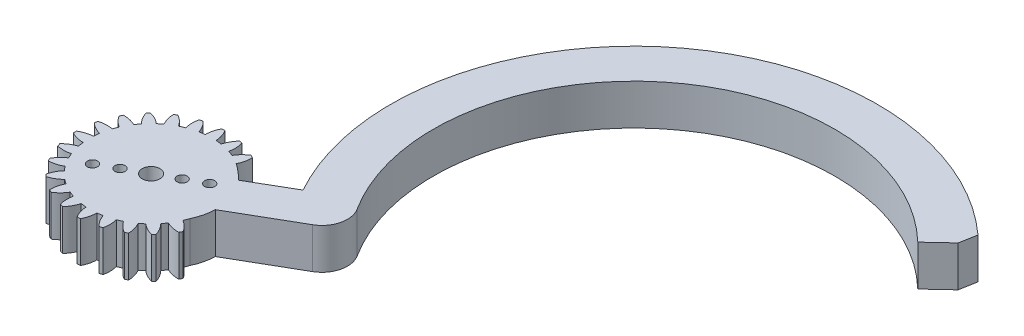
SolidWorks part; units mm, degrees
ref_plane "Alzado" through (0, 0, 0) normal (0, 0, 1) x (1, 0, 0)
ref_plane "Planta" through (0, 0, 0) normal (0, 1, 0) x (1, 0, 0)
ref_plane "Vista lateral" through (0, 0, 0) normal (1, 0, 0) x (0, 0, -1)
sketch "Croquis3" plane through (0, 0, 0) normal (0, 1, 0) x (1, 0, 0)
  line L0 (0, 0) -> (1.7285, 0.2738) construction
  line L1 (0, 0) -> (1.7285, 0.2738) construction
  line L2 (0, 0) -> (1.7285, 0.2738) construction
  line L3 (12.4486, 0.2055) -> (97.8293, 49.5) construction
  line L4 (87.111, 63.804) -> (91.2233, 67.6388)
  line L5 (91.2233, 67.6388) -> (91.8156, 70.9508)
  line L6 (24.5971, 7.2194) -> (12.4486, 0.2055)
  line L7 (12.4396, 0) -> (96.7359, 0) construction
  line L8 (9.7219, 7.516) -> (17.7354, 12.1717)
  line L9 (92.9509, 69.2498) -> (110.2569, 85.3879) construction
  line L10 (29.4133, 10) -> (91.2233, 67.6388) construction
  line L11 (101.0227, 51.3437) -> (128.1865, 67.0268) construction
  line L12 (10.821, -9.8385) -> (10.3914, -10.2913)
  arc A0 (8.3348, 8.7616) -> (6.6617, 10.0924) centre (0, 0) ccw
  arc A1 (6.6617, 10.0924) -> (7.2511, 12.7009) centre (1.8532, 12.5498) ccw
  arc A2 (7.2511, 12.7009) -> (6.7026, 12.9987) centre (0, 0) ccw
  arc A3 (6.7026, 12.9987) -> (4.836, 11.0837) centre (9.5158, 8.3893) ccw
  arc A4 (4.836, 11.0837) -> (3.8226, 11.4727) centre (0, 0) ccw
  arc A5 (3.8226, 11.4727) -> (3.7168, 14.1448) centre (-1.458, 12.6018) ccw
  arc A6 (3.7168, 14.1448) -> (3.1099, 14.2905) centre (0, 0) ccw
  arc A7 (3.1099, 14.2905) -> (1.8025, 11.9577) centre (8.7597, 9.5915) ccw
  arc A8 (1.8025, 11.9577) -> (0.723, 12.0711) centre (0, 0) ccw
  arc A9 (0.723, 12.0711) -> (-0.0708, 14.6248) centre (-4.6699, 11.795) ccw
  arc A10 (-0.0708, 14.6248) -> (-0.6947, 14.6085) centre (0, 0) ccw
  arc A11 (-0.6947, 14.6085) -> (-1.3538, 12.0167) centre (4.0462, 12.0233) ccw
  arc A12 (-1.3538, 12.0167) -> (-2.4259, 11.8469) centre (0, 0) ccw
  arc A13 (-2.4259, 11.8469) -> (-3.8535, 14.1082) centre (-7.5636, 10.1845) ccw
  arc A14 (-3.8535, 14.1082) -> (-4.452, 13.9309) centre (0, 0) ccw
  arc A15 (-4.452, 13.9309) -> (-4.4178, 11.2569) centre (0.7965, 12.6608) ccw
  arc A16 (-4.4178, 11.2569) -> (-5.4094, 10.8154) centre (0, 0) ccw
  arc A17 (-5.4094, 10.8154) -> (-7.3737, 12.6301) centre (-9.9418, 7.8798) ccw
  arc A18 (-7.3737, 12.6301) -> (-7.9059, 12.304) centre (0, 0) ccw
  arc A19 (-7.9059, 12.304) -> (-7.1808, 9.7299) centre (-2.5075, 12.4356) ccw
  arc A20 (-7.1808, 9.7299) -> (-8.0243, 9.0468) centre (0, 0) ccw
  arc A21 (-8.0243, 9.0468) -> (-10.3914, 10.2913) centre (-11.6425, 5.0382) ccw
  arc A22 (-10.3914, 10.2913) -> (-10.821, 9.8385) centre (0, 0) ccw
  arc A23 (-10.821, 9.8385) -> (-9.4544, 7.5398) centre (-5.6406, 11.3628) ccw
  arc A24 (-9.4544, 7.5398) -> (-10.0924, 6.6617) centre (0, 0) ccw
  arc A25 (-10.0924, 6.6617) -> (-12.7009, 7.2511) centre (-12.5498, 1.8532) ccw
  arc A26 (-12.7009, 7.2511) -> (-12.9987, 6.7026) centre (0, 0) ccw
  arc A27 (-12.9987, 6.7026) -> (-11.0837, 4.836) centre (-8.3893, 9.5158) ccw
  arc A28 (-11.0837, 4.836) -> (-11.4727, 3.8226) centre (0, 0) ccw
  arc A29 (-11.4727, 3.8226) -> (-14.1448, 3.7168) centre (-12.6018, -1.458) ccw
  arc A30 (-14.1448, 3.7168) -> (-14.2905, 3.1099) centre (0, 0) ccw
  arc A31 (-14.2905, 3.1099) -> (-11.9577, 1.8025) centre (-10.5663, 7.0202) ccw
  arc A32 (-11.9577, 1.8025) -> (-12.0711, 0.723) centre (0, 0) ccw
  arc A33 (-12.0711, 0.723) -> (-14.6248, -0.0708) centre (-11.795, -4.6699) ccw
  arc A34 (-14.6248, -0.0708) -> (-14.6085, -0.6947) centre (0, 0) ccw
  arc A35 (-14.6085, -0.6947) -> (-12.0167, -1.3538) centre (-12.0233, 4.0462) ccw
  arc A36 (-12.0167, -1.3538) -> (-11.8469, -2.4259) centre (0, 0) ccw
  arc A37 (-11.8469, -2.4259) -> (-14.1082, -3.8535) centre (-10.1845, -7.5636) ccw
  arc A38 (-14.1082, -3.8535) -> (-13.9309, -4.452) centre (0, 0) ccw
  arc A39 (-13.9309, -4.452) -> (-11.2569, -4.4178) centre (-12.6608, 0.7965) ccw
  arc A40 (-11.2569, -4.4178) -> (-10.8154, -5.4094) centre (0, 0) ccw
  arc A41 (-10.8154, -5.4094) -> (-12.6301, -7.3737) centre (-7.8798, -9.9418) ccw
  arc A42 (-12.6301, -7.3737) -> (-12.304, -7.9059) centre (0, 0) ccw
  arc A43 (-12.304, -7.9059) -> (-9.7299, -7.1808) centre (-12.4356, -2.5075) ccw
  arc A44 (-9.7299, -7.1808) -> (-9.0468, -8.0243) centre (0, 0) ccw
  arc A45 (-9.0468, -8.0243) -> (-10.2913, -10.3914) centre (-5.0382, -11.6425) ccw
  arc A46 (-10.2913, -10.3914) -> (-9.8385, -10.821) centre (0, 0) ccw
  arc A47 (-9.8385, -10.821) -> (-7.5398, -9.4544) centre (-11.3628, -5.6406) ccw
  arc A48 (-7.5398, -9.4544) -> (-6.6617, -10.0924) centre (0, 0) ccw
  arc A49 (-6.6617, -10.0924) -> (-7.2511, -12.7009) centre (-1.8532, -12.5498) ccw
  arc A50 (-7.2511, -12.7009) -> (-6.7026, -12.9987) centre (0, 0) ccw
  arc A51 (-6.7026, -12.9987) -> (-4.836, -11.0837) centre (-9.5158, -8.3893) ccw
  arc A52 (-4.836, -11.0837) -> (-3.8226, -11.4727) centre (0, 0) ccw
  arc A53 (-3.8226, -11.4727) -> (-3.7168, -14.1448) centre (1.458, -12.6018) ccw
  arc A54 (-3.7168, -14.1448) -> (-3.1099, -14.2905) centre (0, 0) ccw
  arc A55 (-3.1099, -14.2905) -> (-1.8025, -11.9577) centre (-7.0202, -10.5663) ccw
  arc A56 (-1.8025, -11.9577) -> (-0.723, -12.0711) centre (0, 0) ccw
  arc A57 (-0.723, -12.0711) -> (0.0708, -14.6248) centre (4.6699, -11.795) ccw
  arc A58 (0.0708, -14.6248) -> (0.6947, -14.6085) centre (0, 0) ccw
  arc A59 (0.6947, -14.6085) -> (1.3538, -12.0167) centre (-4.0462, -12.0233) ccw
  arc A60 (1.3538, -12.0167) -> (2.4259, -11.8469) centre (0, 0) ccw
  arc A61 (2.4259, -11.8469) -> (3.8535, -14.1082) centre (7.5636, -10.1845) ccw
  arc A62 (3.8535, -14.1082) -> (4.452, -13.9309) centre (0, 0) ccw
  arc A63 (4.452, -13.9309) -> (4.4178, -11.2569) centre (-0.7965, -12.6608) ccw
  arc A64 (4.4178, -11.2569) -> (5.4094, -10.8154) centre (0, 0) ccw
  arc A65 (5.4094, -10.8154) -> (7.3737, -12.6301) centre (9.9418, -7.8798) ccw
  arc A66 (7.3737, -12.6301) -> (7.9059, -12.304) centre (0, 0) ccw
  arc A67 (7.9059, -12.304) -> (7.1808, -9.7299) centre (2.5075, -12.4356) ccw
  arc A68 (7.1808, -9.7299) -> (8.0243, -9.0468) centre (0, 0) ccw
  arc A69 (8.0243, -9.0468) -> (10.3914, -10.2913) centre (11.6425, -5.0382) ccw
  arc A71 (10.821, -9.8385) -> (9.4544, -7.5398) centre (5.6406, -11.3628) ccw
  arc A72 (9.4544, -7.5398) -> (10.0924, -6.6617) centre (0, 0) ccw
  arc A73 (10.0924, -6.6617) -> (12.7009, -7.2511) centre (12.5498, -1.8532) ccw
  arc A74 (12.7009, -7.2511) -> (12.9987, -6.7026) centre (0, 0) ccw
  arc A75 (12.9987, -6.7026) -> (11.0837, -4.836) centre (8.3893, -9.5158) ccw
  arc A76 (11.0837, -4.836) -> (11.4727, -3.8226) centre (0, 0) ccw
  circle A77 centre (0, 0) radius 1.75
  arc A78 (-11.0837, 4.836) -> (-11.4727, 3.8226) centre (0, 0) ccw construction
  arc A79 (-11.0837, 4.836) -> (-11.4727, 3.8226) centre (0, 0) ccw
  arc A80 (-9.4544, 7.5398) -> (-10.0924, 6.6617) centre (0, 0) ccw
  arc A81 (-9.4544, 7.5398) -> (-10.0924, 6.6617) centre (0, 0) ccw construction
  arc A82 (-7.1808, 9.7299) -> (-8.0243, 9.0468) centre (0, 0) ccw
  arc A83 (-7.1808, 9.7299) -> (-8.0243, 9.0468) centre (0, 0) ccw construction
  arc A84 (-4.4178, 11.2569) -> (-5.4094, 10.8154) centre (0, 0) ccw
  arc A85 (-4.4178, 11.2569) -> (-5.4094, 10.8154) centre (0, 0) ccw construction
  arc A86 (-1.3538, 12.0167) -> (-2.4259, 11.8469) centre (0, 0) ccw
  arc A87 (-1.3538, 12.0167) -> (-2.4259, 11.8469) centre (0, 0) ccw construction
  arc A88 (1.8025, 11.9577) -> (0.723, 12.0711) centre (0, 0) ccw
  arc A89 (1.8025, 11.9577) -> (0.723, 12.0711) centre (0, 0) ccw construction
  arc A90 (4.836, 11.0837) -> (3.8226, 11.4727) centre (0, 0) ccw
  arc A91 (4.836, 11.0837) -> (3.8226, 11.4727) centre (0, 0) ccw construction
  arc A92 (8.3348, 8.7616) -> (6.6617, 10.0924) centre (0, 0) ccw
  arc A93 (8.3348, 8.7616) -> (6.6617, 10.0924) centre (0, 0) ccw construction
  arc A94 (8.3348, 8.7616) -> (9.7219, 7.516) centre (2.2158, 0.5525) cw
  arc A95 (12.4486, 0.2055) -> (11.4727, -3.8226) centre (2.2158, 0.5525) cw
  arc A96 (9.4544, -7.5398) -> (10.0924, -6.6617) centre (0, 0) ccw
  arc A97 (9.4544, -7.5398) -> (10.0924, -6.6617) centre (0, 0) ccw construction
  arc A98 (7.1808, -9.7299) -> (8.0243, -9.0468) centre (0, 0) ccw
  arc A99 (7.1808, -9.7299) -> (8.0243, -9.0468) centre (0, 0) ccw construction
  arc A100 (4.4178, -11.2569) -> (5.4094, -10.8154) centre (0, 0) ccw
  arc A101 (4.4178, -11.2569) -> (5.4094, -10.8154) centre (0, 0) ccw construction
  arc A102 (1.3538, -12.0167) -> (2.4259, -11.8469) centre (0, 0) ccw
  arc A103 (1.3538, -12.0167) -> (2.4259, -11.8469) centre (0, 0) ccw construction
  arc A104 (-1.8025, -11.9577) -> (-0.723, -12.0711) centre (0, 0) ccw
  arc A105 (-1.8025, -11.9577) -> (-0.723, -12.0711) centre (0, 0) ccw construction
  arc A106 (-4.836, -11.0837) -> (-3.8226, -11.4727) centre (0, 0) ccw
  arc A107 (-4.836, -11.0837) -> (-3.8226, -11.4727) centre (0, 0) ccw construction
  arc A108 (-7.5398, -9.4544) -> (-6.6617, -10.0924) centre (0, 0) ccw
  arc A109 (-7.5398, -9.4544) -> (-6.6617, -10.0924) centre (0, 0) ccw construction
  arc A110 (-9.7299, -7.1808) -> (-9.0468, -8.0243) centre (0, 0) ccw
  arc A111 (-9.7299, -7.1808) -> (-9.0468, -8.0243) centre (0, 0) ccw construction
  arc A112 (-11.2569, -4.4178) -> (-10.8154, -5.4094) centre (0, 0) ccw
  arc A113 (-11.2569, -4.4178) -> (-10.8154, -5.4094) centre (0, 0) ccw construction
  arc A114 (-12.0167, -1.3538) -> (-11.8469, -2.4259) centre (0, 0) ccw construction
  arc A115 (-12.0167, -1.3538) -> (-11.8469, -2.4259) centre (0, 0) ccw
  arc A116 (-11.9577, 1.8025) -> (-12.0711, 0.723) centre (0, 0) ccw construction
  arc A117 (-11.9577, 1.8025) -> (-12.0711, 0.723) centre (0, 0) ccw
  arc A118 (26.319, 14.2282) -> (87.111, 63.804) centre (59.672, 35.3901) cw
  arc A119 (91.8156, 70.9508) -> (17.7354, 12.1717) centre (59.672, 35.3901) ccw
  arc A120 (24.5971, 7.2194) -> (26.319, 14.2282) centre (22.0971, 11.5495) ccw
  dimension "D4" = 39.5
  dimension "D5" = 5
  dimension "D2" = 10
  dimension "D3" = 13
extrude "Saliente-Extruir2" add sketch "Croquis3" along normal blind 8
sketch "Croquis4" plane through (0, 8, 0) normal (0, 1, 0) x (1, 0, 0)
  line L0 (0, 0) -> (-23.0624, -12.6745) construction
  line L1 (-23.0624, -12.6745) -> (30.9497, 17.0092) construction
  circle A0 centre (3.9437, 2.1673) radius 1
  circle A1 centre (-3.9437, -2.1673) radius 1
  circle A2 centre (7.4492, 4.0939) radius 1
  circle A3 centre (-7.4492, -4.0939) radius 1
  dimension "D1" = 2
  dimension "D2" = 2
  dimension "D5" = 2
  dimension "D6" = 2
  dimension "D3" = 4.5
  dimension "D4" = 4.5
  dimension "D7" = 4
  dimension "D8" = 4
extrude "Cortar-Extruir1" cut sketch "Croquis4" against normal blind 8
sketch "Croquis5" plane through (0, 0, 0) normal (0, -1, 0) x (1, 0, 0)
  line L0 (-7.4492, 4.0939) -> (7.4492, -4.0939) construction
  line L1 (-5.7635, 7.1612) -> (9.1349, -1.0266)
  line L2 (-9.1349, 1.0266) -> (5.7635, -7.1612)
  arc A0 (-5.7635, 7.1612) -> (-9.1349, 1.0266) centre (-7.4492, 4.0939) ccw
  arc A1 (5.7635, -7.1612) -> (9.1349, -1.0266) centre (7.4492, -4.0939) ccw
  point P4 (0, 0)
  dimension "D1" = 3.5
extrude "Cortar-Extruir2" cut sketch "Croquis5" against normal blind 4
